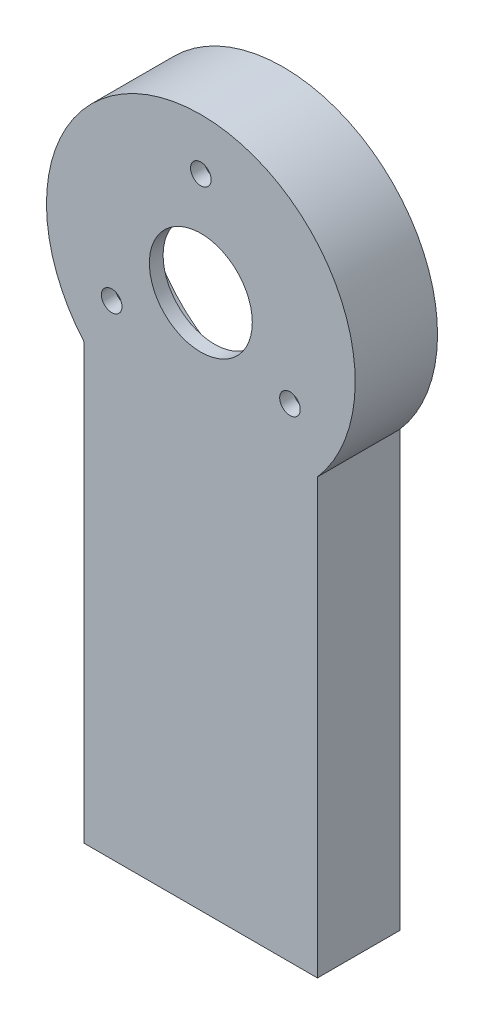
SolidWorks part; units mm, degrees
ref_plane "Front Plane" through (0, 0, 0) normal (0, 0, 1) x (1, 0, 0)
ref_plane "Top Plane" through (0, 0, 0) normal (0, 1, 0) x (1, 0, 0)
ref_plane "Right Plane" through (0, 0, 0) normal (1, 0, 0) x (0, 0, -1)
sketch "Sketch1" plane through (0, 0, 0) normal (0, 0, 1) x (1, 0, 0)
  line L0 (-17, -14.7394) -> (-17, -78)
  line L1 (-17, -78) -> (17, -78)
  line L2 (17, -14.7394) -> (17, -78)
  line L3 (0, 0) -> (0, -85.937) construction
  circle A0 centre (0, 0) radius 22.5
  arc A1 (-17, -14.7394) -> (17, -14.7394) centre (0, 0) ccw
  dimension "D2" = 45
  dimension "D1" = 34
  dimension "D3" = 78
extrude "Boss-Extrude1" add sketch "Sketch1" along normal blind 12
sketch "Sketch2" plane through (0, 0, 0) normal (0, 0, -1) x (-1, 0, 0)
  circle A0 centre (0, 0) radius 21
  dimension "D1" = 42
extrude "Cut-Extrude1" cut sketch "Sketch2" against normal blind 10
sketch "Sketch3" plane through (0, 0, 12) normal (0, 0, 1) x (1, 0, 0)
  line L0 (0, 0) -> (0, 15) construction
  circle A0 centre (0, 15) radius 1.5
  circle A1 centre (12.9904, -7.5) radius 1.5
  circle A2 centre (-12.9904, -7.5) radius 1.5
  circle A3 centre (0, 0) radius 7.5
  point P10 (0, 0)
  dimension "D1" = 3
  dimension "D2" = 15
  dimension "D4" = 15
  dimension "D3" = 3
extrude "Cut-Extrude2" cut sketch "Sketch3" against normal through all
